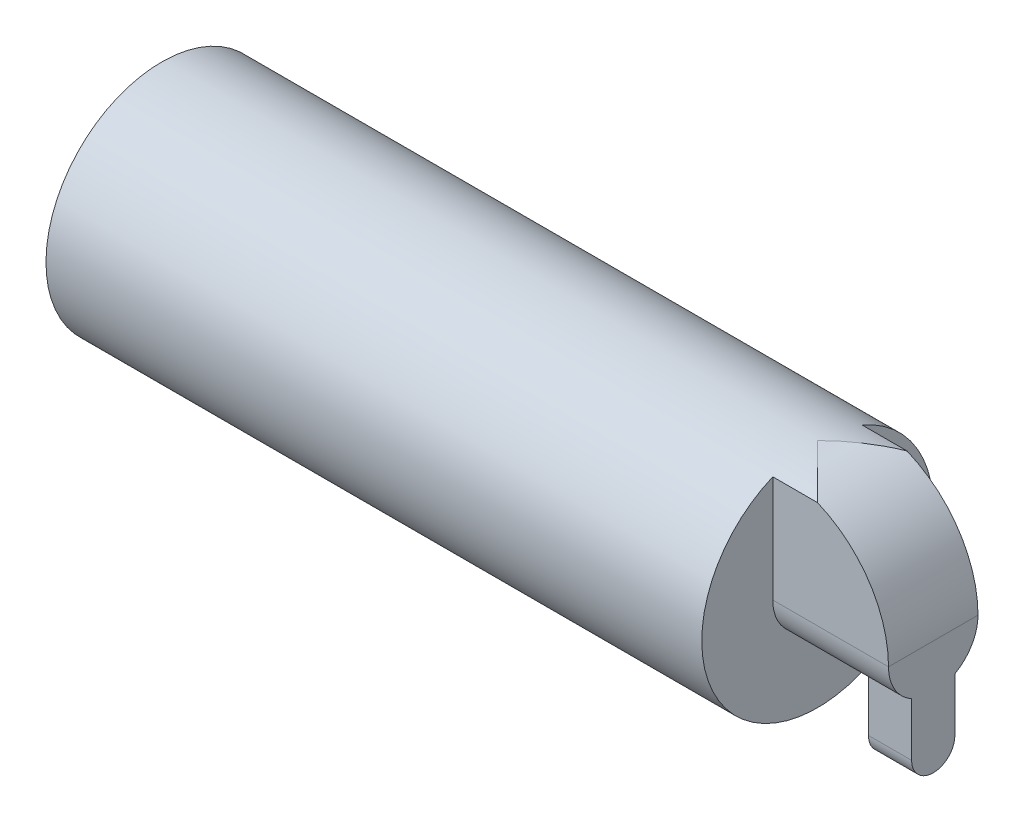
SolidWorks part; units mm, degrees
ref_plane "Front Plane" through (0, 0, 0) normal (0, 0, 1) x (1, 0, 0)
ref_plane "Top Plane" through (0, 0, 0) normal (0, 1, 0) x (1, 0, 0)
ref_plane "Right Plane" through (0, 0, 0) normal (1, 0, 0) x (0, 0, -1)
sketch "Sketch1" plane through (0, 0, 0) normal (1, 0, 0) x (0, 0, -1)
  circle A0 centre (0, 0) radius 7.5
  dimension "D1" = 15
extrude "Boss-Extrude1" add sketch "Sketch1" along normal blind 42.5
sketch "Sketch3" plane through (0, 0, 0) normal (1, 0, 0) x (0, 0, -1)
  line L0 (-2.9, 0) -> (-2.9, 6.9166)
  line L2 (2.9, 0) -> (2.9, 6.9166)
  arc A0 (-2.9, 0) -> (2.9, 0) centre (0, 0) ccw
  arc A1 (2.9, 6.9166) -> (-2.9, 6.9166) centre (0, 0) ccw
  circle A2 centre (0, 0) radius 7.5 construction
  dimension "D1" = 5.8
extrude "Boss-Extrude2" add sketch "Sketch3" along normal blind 50
sketch "Sketch4" plane through (50, 0, 0) normal (1, 0, 0) x (0, 0, -1)
  line L0 (-1.4, -6) -> (-1.4, 0)
  line L1 (-1.4, 0) -> (1.4, 0)
  line L2 (1.4, 0) -> (1.4, -6)
  line L3 (0, -6) -> (0, 0) construction
  arc A0 (-1.4, -6) -> (1.4, -6) centre (0, -6) ccw
  arc A1 (-2.9, 0) -> (2.9, 0) centre (0, 0) ccw construction
  dimension "D1" = 2.8
  dimension "D2" = 6
extrude "Boss-Extrude3" add sketch "Sketch4" against normal blind 2.8
sketch "Sketch6" plane through (0, 0, 0) normal (0, 0, 1) x (1, 0, 0)
  line L0 (0, 0) -> (80.8642, 0) construction
  line L1 (50, 7.5) -> (0, 7.5) construction
  line L2 (50, 0) -> (50, 7.5)
  line L3 (50, 7.5) -> (42.5, 7.5)
  line L4 (0, 0) -> (0, 19.7679) construction
  line L5 (-50, 7.5) -> (-42.5, 7.5)
  line L6 (-50, 0) -> (-50, 7.5)
  arc A0 (50, 0) -> (42.5, 7.5) centre (42.5, 0) ccw
  arc A1 (-50, 0) -> (-42.5, 7.5) centre (-42.5, 0) cw
extrude "Cut-Extrude1" cut sketch "Sketch6" against normal blind 7.5 and the other way blind 7.5
sketch "Sketch7" plane through (0, 0, 0) normal (-1, 0, 0) x (0, 0, 1)
  line L0 (-4, 0) -> (-2.8284, 1.1716)
  line L1 (-4, 0) -> (-2.8284, -1.1716)
  line L2 (0, 4) -> (1.1716, 2.8284)
  line L3 (0, -4) -> (1.1716, -2.8284)
  line L4 (0, 0) -> (0, 2.4739) construction
  line L5 (-4, 0) -> (4, 0) construction
  line L6 (-1.1716, 2.8284) -> (0, 4)
  line L7 (-2.8284, 2.8284) -> (-1.1716, 2.8284)
  line L8 (-2.8284, 2.8284) -> (-2.8284, 1.1716)
  line L9 (-2.8284, -2.8284) -> (-1.1716, -2.8284)
  line L10 (2.8284, 2.8284) -> (2.8284, 1.1716)
  line L11 (-2.8284, -1.1716) -> (-2.8284, -2.8284)
  line L12 (-1.1716, -2.8284) -> (0, -4)
  line L13 (1.1716, -2.8284) -> (2.8284, -2.8284)
  line L14 (2.8284, -1.1716) -> (4, 0)
  line L15 (2.8284, -1.1716) -> (2.8284, -2.8284)
  line L16 (2.8284, 1.1716) -> (4, 0)
  line L17 (1.1716, 2.8284) -> (2.8284, 2.8284)
  circle A0 centre (0, 0) radius 7.5 construction
  point P3 (-3.0394, -3.177)
  point P16 (-3.2104, 2.4375)
  point P23 (0, 0)
  dimension "D1" = 4
  dimension "D2" = 4
extrude "Cut-Extrude2" cut sketch "Sketch7" against normal blind 8
